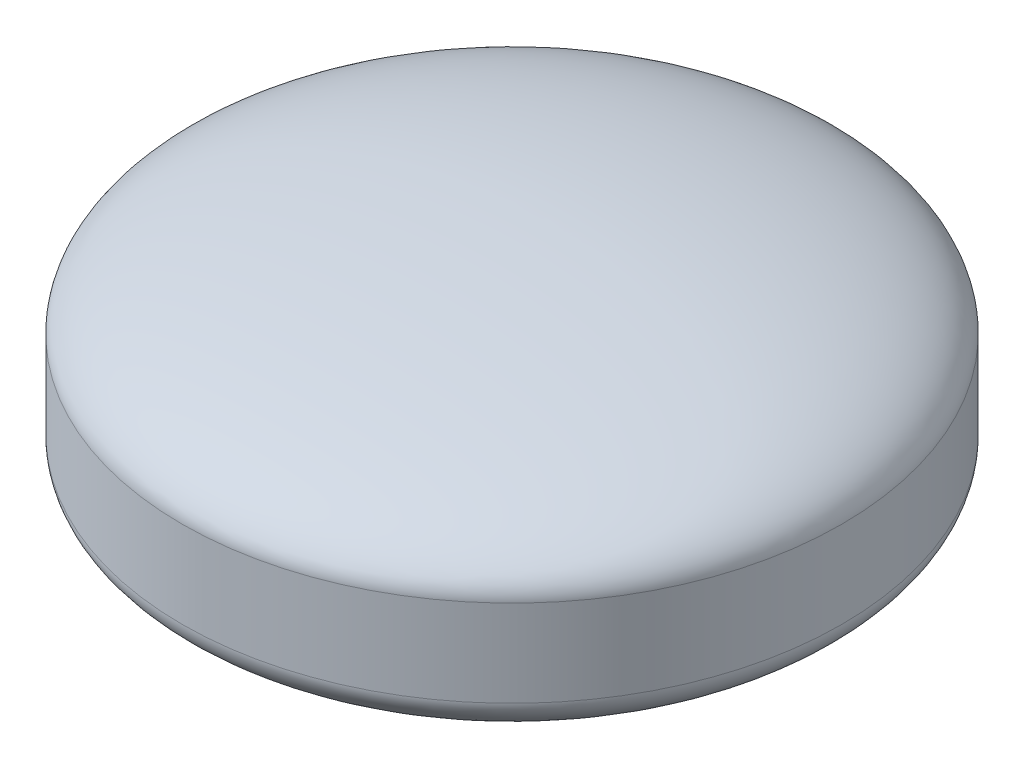
SolidWorks part; units mm, degrees
other "마크업1"
sketch "스케치3" plane through (-9.5, -3.75, -9.5) normal (0, 0, -1) x (-1, 0, 0)
ref_plane "정면도" through (0, 0, 0) normal (0, 0, 1) x (1, 0, 0)
ref_plane "평면도" through (0, 0, 0) normal (0, 1, 0) x (1, 0, 0)
ref_plane "우측면도" through (0, 0, 0) normal (1, 0, 0) x (0, 0, -1)
sketch "스케치2" plane through (0, 0, 0) normal (0, 0, 1) x (1, 0, 0)
  line L1 (0, 0) -> (-9.5, 0)
  line L2 (-9.5, 0) -> (-9.5, 1.25)
  line L3 (-9.5, 1.25) -> (0, 1.25)
  line L9 (0, 0) -> (0, 3.75) construction
  ellipse E0 centre (0, 1.25) end of major axis (-9.5, 1.25) minor radius 2.5 (0, 3.75) -> (-9.5, 1.25) ccw
  dimension "D1" = 9.5
  dimension "D2" = 1.25
  dimension "D3" = 2.5
revolve "회전3" add sketch "스케치2" angle 360 about L9
mirror "대칭 복사1" about plane through (0, 0, 0) normal (0, 1, 0) of "회전3"
sketch "스케치4" plane through (0, 0, 0) normal (1, 0, 0) x (0, 0, -1)
  ellipse E0 centre (0, 1.25) end of major axis (-9.5, 1.25) minor radius 2.5 (0, 3.75) -> (-9.5, 1.25) ccw construction
  ellipse E1 centre (0, 1.25) end of major axis (-9.5, 1.25) minor radius 2.5 (0, 3.75) -> (-9.5, 1.25) ccw
  ellipse E2 centre (0, -1.25) end of major axis (-9.5, -1.25) minor radius 2.5 (-9.5, -1.25) -> (0, -3.75) ccw construction
  ellipse E3 centre (0, -1.25) end of major axis (-9.5, -1.25) minor radius 2.5 (-9.5, -1.25) -> (0, -3.75) ccw
